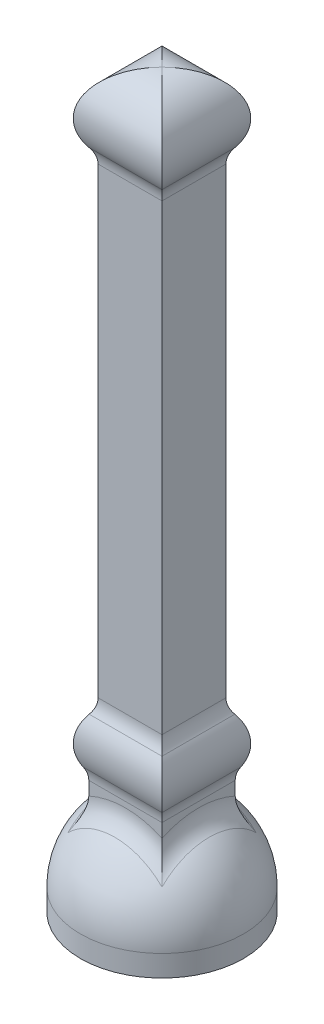
SolidWorks part; units mm, degrees
ref_plane "Front" through (0, 0, 0) normal (0, 0, 1) x (1, 0, 0)
ref_plane "Top" through (0, 0, 0) normal (0, 1, 0) x (1, 0, 0)
ref_plane "Right" through (0, 0, 0) normal (1, 0, 0) x (0, 0, -1)
sketch "Sketch1" plane through (0, 0, 0) normal (0, 1, 0) x (1, 0, 0)
  line L1 (-1.25, 1.25) -> (1.25, 1.25)
  line L2 (-1.25, 1.25) -> (-1.25, -1.25)
  line L3 (-1.25, -1.25) -> (1.25, -1.25)
  line L4 (1.25, 1.25) -> (1.25, -1.25)
  line L5 (-1.25, 1.25) -> (1.25, -1.25) construction
  line L6 (-1.25, -1.25) -> (1.25, 1.25) construction
  point P0 (0, 0)
  dimension "D1" = 2.5
  dimension "D2" = 2.5
extrude "Boss-Extrude1" add sketch "Sketch1" along normal blind 20
sketch "Sketch3" plane through (0, 0, 0) normal (1, 0, 0) x (0, 0, -1)
  line L1 (-1.25, 20) -> (1.25, 20) construction
  line L2 (-1.25, 20) -> (-1.25, 0) construction
  line L5 (0, 20) -> (-2.2869, 20)
  line L6 (-0.9, 17.8825) -> (-0.9, 4.3675)
  line L7 (-2.2869, 20) -> (-2.2869, 0)
  line L11 (-1.0311, 2.7933) -> (-1.0311, 0)
  line L12 (-1.25, 20) -> (-1.25, 0) construction
  line L13 (-1.0311, 0) -> (-2.2869, 0)
  arc A0 (0, 20) -> (-0.9, 17.8825) centre (0, 18.75) ccw
  arc A1 (-0.9, 4.3675) -> (-1.0311, 2.7933) centre (0, 3.5) ccw
  point P0 (-1.25, 20)
  dimension "D4" = 1.25
  dimension "D1" = 3.5
  dimension "D6" = 0
  dimension "D2" = 0.35
  dimension "D5" = 1.25
  dimension "D3" = 0.35
extrude "Cut-Extrude1" cut sketch "Sketch3" against normal through all both and the other way through all
sketch "Sketch5" plane through (0, 0, 0) normal (1, 0, 0) x (0, 0, -1)
  line L0 (0, 0) -> (0, 22.2629) construction
pattern_circular "CirPattern1" count 4 over 360 about axis through (0, 0, 0) along (0, 1, 0) of "Cut-Extrude1"
sketch "Sketch2" plane through (0, 0, 0) normal (1, 0, 0) x (0, 0, -1)
  line L0 (2.2963, 0) -> (0, 0)
  line L1 (0, 0) -> (0, 2.2963)
  line L2 (0, 0) -> (0, 8.9194) construction
  arc A0 (2.2963, 0) -> (0, 2.2963) centre (0, 0) ccw
revolve "Revolve1" add sketch "Sketch2" angle 360 about L2
fillet "Fillet1" radius 0.7 16 edges at (0.9, 4.3675, 0) (0, 4.3675, -0.9) (-0.9, 4.3675, 0) (0, 4.3675, 0.9) (0, 17.8825, -0.9) (-0.9, 17.8825, 0) (0, 17.8825, 0.9) (0.9, 17.8825, 0) (-1.0311, 2.7933, 0) (0, 2.7933, 1.0311) (1.0311, 2.7933, 0) (0, 2.7933, -1.0311) (0, 2.0518, -1.0311) (-1.0311, 2.0518, 0) (0, 2.0518, 1.0311) (1.0311, 2.0518, 0)
sketch "Sketch6" plane through (0, 0, 0) normal (0, -1, 0) x (1, 0, 0)
  circle A0 centre (0, 0) radius 2.2963
extrude "Boss-Extrude2" add sketch "Sketch6" along normal blind 0.6
